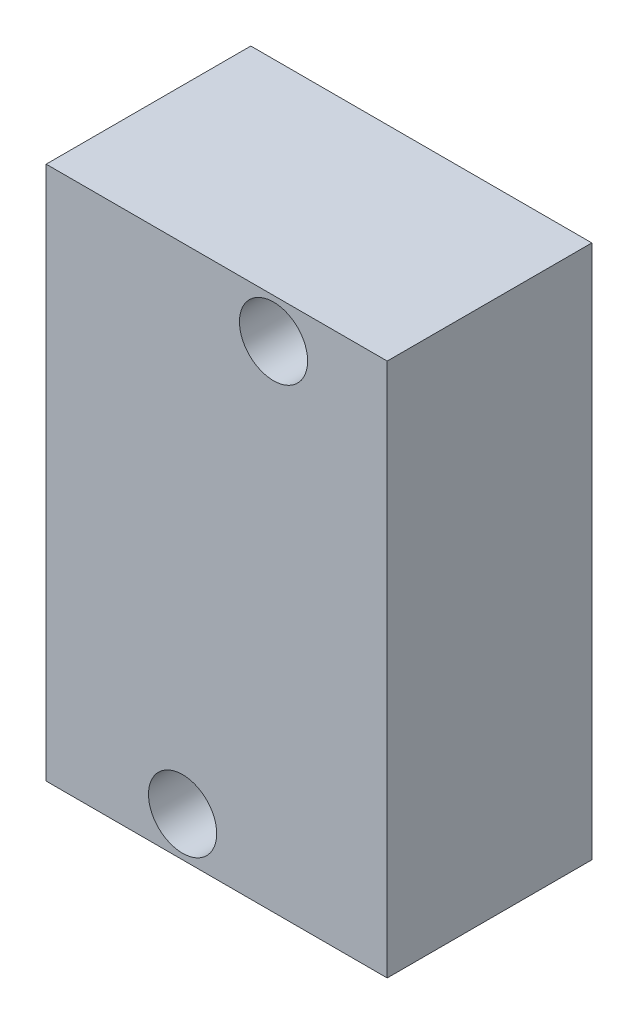
SolidWorks part; units mm, degrees
ref_plane "Front Plane" through (0, 0, 0) normal (0, 0, 1) x (1, 0, 0)
ref_plane "Top Plane" through (0, 0, 0) normal (0, 1, 0) x (1, 0, 0)
ref_plane "Right Plane" through (0, 0, 0) normal (1, 0, 0) x (0, 0, -1)
sketch "Sketch1" plane through (0, 0, 0) normal (0, 0, 1) x (1, 0, 0)
  line L1 (-6.2097, 5.736) -> (12.8403, 5.736)
  line L2 (-6.2097, 5.736) -> (-6.2097, -24.109)
  line L3 (-6.2097, -24.109) -> (12.8403, -24.109)
  line L4 (12.8403, 5.736) -> (12.8403, -24.109)
  dimension "D1" = 19.05
  dimension "D2" = 29.845
extrude "Boss-Extrude1" add sketch "Sketch1" along normal blind 11.43
sketch "Sketch2" plane through (0, 0, 11.43) normal (0, 0, 1) x (1, 0, 0)
  line L0 (-6.2097, -24.109) -> (12.8403, -24.109) construction
  line L1 (-6.2097, 5.736) -> (-6.2097, -24.109) construction
  circle A0 centre (6.4903, 3.5135) radius 1.905
  circle A1 centre (1.4103, -21.8865) radius 1.905
  dimension "D2" = 3.81
  dimension "D1" = 5.08
  dimension "D3" = 25.4
  dimension "D4" = 2.2225
  dimension "D5" = 7.62
extrude "Cut-Extrude1" cut sketch "Sketch2" against normal blind 11.43
